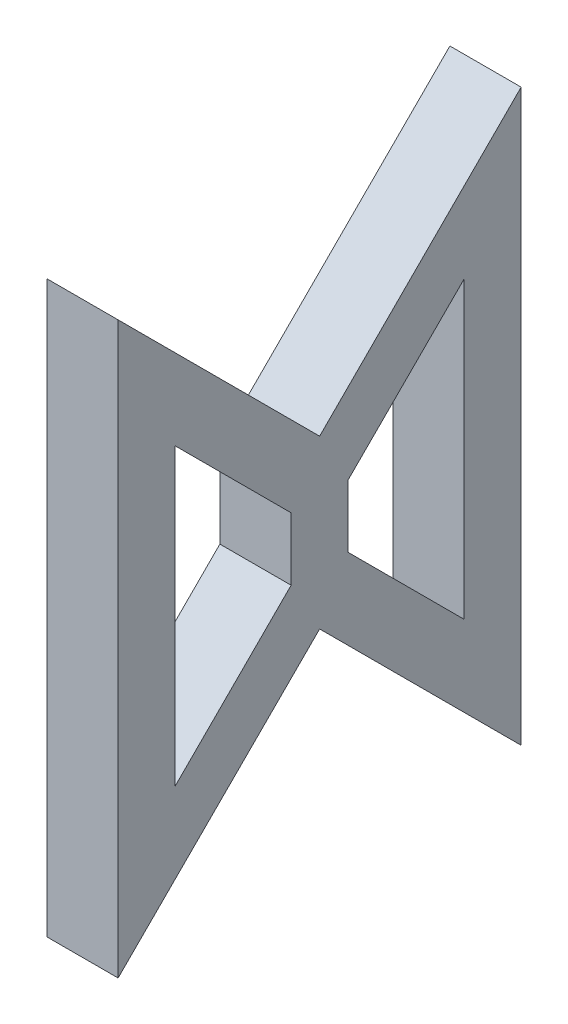
SolidWorks part; units mm, degrees
ref_plane "Front Plane" through (0, 0, 0) normal (0, 0, 1) x (1, 0, 0)
ref_plane "Top Plane" through (0, 0, 0) normal (0, 1, 0) x (1, 0, 0)
ref_plane "Right Plane" through (0, 0, 0) normal (1, 0, 0) x (0, 0, -1)
sketch "Sketch1" plane through (0, 0, 0) normal (1, 0, 0) x (0, 0, -1)
  line L0 (14.1421, 0) -> (14.1421, -40) construction
  line L1 (0, 0) -> (28.2843, 0)
  line L2 (0, 0) -> (0, -40)
  line L3 (0, -40) -> (28.2843, -40)
  line L4 (28.2843, 0) -> (28.2843, -40)
  line L5 (0, 0) -> (14.1421, -14.1421)
  line L6 (14.1421, -14.1421) -> (28.2843, 0)
  line L7 (0, -20) -> (28.2843, -20) construction
  line L8 (14.1421, -25.8579) -> (28.2843, -40)
  line L9 (0, -40) -> (14.1421, -25.8579)
  dimension "D1" = 45
  dimension "D2" = 20
  dimension "D3" = 40
extrude "Boss-Extrude1" add sketch "Sketch1" along normal blind 5 contours L2 L9 L8 L4 L6 L5
sketch "Sketch2" plane through (5, 0, 0) normal (1, 0, 0) x (0, 0, -1)
  line L6 (14.1421, -14.1421) -> (14.1421, -25.8579) construction
  line L8 (12.1421, -25) -> (16.1421, -25)
  line L9 (12.1421, -25) -> (12.1421, -15)
  line L10 (12.1421, -15) -> (16.1421, -15)
  line L11 (16.1421, -25) -> (16.1421, -15)
  line L12 (4, -9.6569) -> (4, -30.3431)
  line L13 (4, -30.3431) -> (14.1421, -20.201)
  line L14 (14.1421, -20.201) -> (24.2843, -30.3431)
  line L15 (24.2843, -30.3431) -> (24.2843, -9.6569)
  line L16 (24.2843, -9.6569) -> (14.1421, -19.799)
  line L17 (14.1421, -19.799) -> (4, -9.6569)
  line L18 (4, -9.6569) -> (4, -30.3431)
  line L19 (4, -30.3431) -> (14.1421, -20.201)
  line L20 (14.1421, -20.201) -> (24.2843, -30.3431)
  line L21 (24.2843, -30.3431) -> (24.2843, -9.6569)
  line L22 (24.2843, -9.6569) -> (14.1421, -19.799)
  line L23 (14.1421, -19.799) -> (4, -9.6569)
  line L24 (12.1421, -25) -> (16.1421, -15) construction
  line L25 (12.1421, -15) -> (16.1421, -25) construction
  point P3 (14.1421, -20)
  dimension "D2" = 10
  dimension "D3" = 4
  dimension "D1" = 4
extrude "Cut-Extrude1" cut sketch "Sketch2" against normal through all contours L9 L23 L18 L19 | L21 L22 L11 L20
